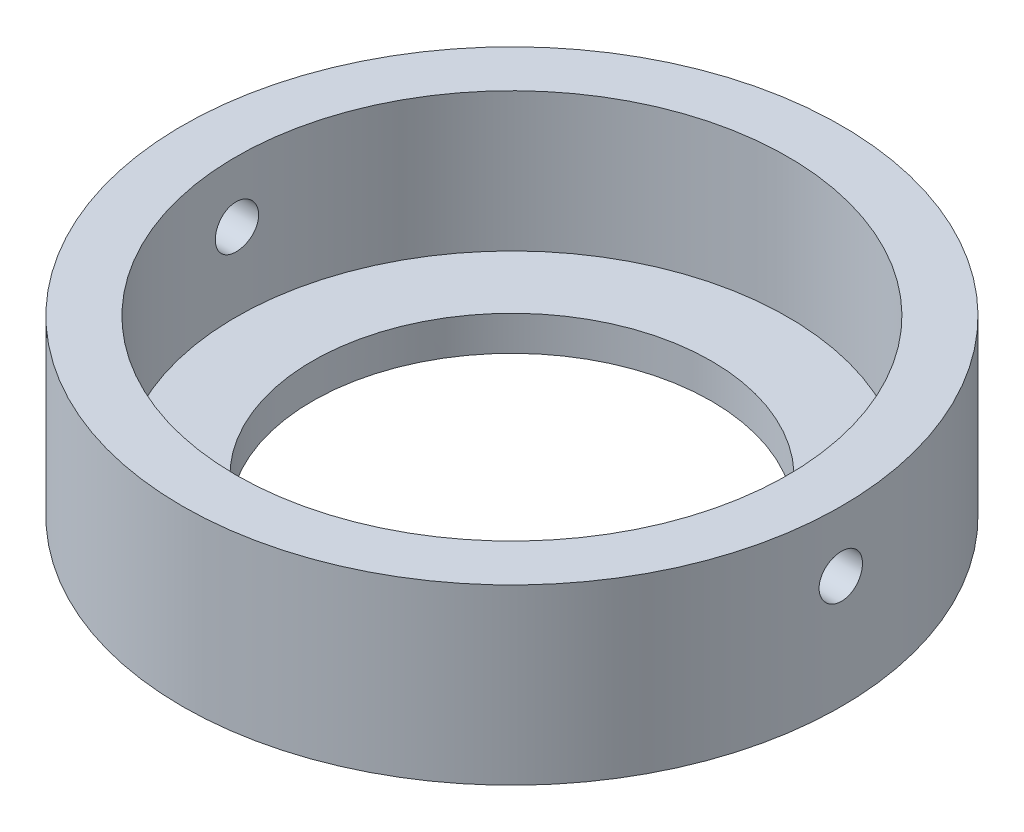
SolidWorks part; units mm, degrees
ref_plane "前视基准面" through (0, 0, 0) normal (0, 0, 1) x (1, 0, 0)
ref_plane "上视基准面" through (0, 0, 0) normal (0, 1, 0) x (1, 0, 0)
ref_plane "右视基准面" through (0, 0, 0) normal (1, 0, 0) x (0, 0, -1)
other "Configuration Table"
sketch "草图1" plane through (0, 0, 0) normal (0, 1, 0) x (1, 0, 0)
  circle A0 centre (0, 0) radius 19
  dimension "D1" = 38
extrude "凸台-拉伸1" add sketch "草图1" along normal blind 2
sketch "草图2" plane through (0, 2, 0) normal (0, 1, 0) x (1, 0, 0)
  circle A0 centre (0, 0) radius 19
  circle A1 centre (0, 0) radius 15.9
  dimension "D1" = 31.8
extrude "凸台-拉伸2" add sketch "草图2" along normal blind 8
sketch "草图3" plane through (0, 0, 0) normal (0, -1, 0) x (1, 0, 0)
  circle A0 centre (0, 0) radius 11.5
  dimension "D1" = 23
extrude "切除-拉伸1" cut sketch "草图3" against normal blind 6
sketch "草图4" plane through (0, 10, 0) normal (0, 1, 0) x (1, 0, 0)
  line L0 (0, 0) -> (0, 19) construction
  line L1 (0, 0) -> (19, 0) construction
  line L2 (0, 0) -> (-19, 0) construction
  circle A0 centre (0, 0) radius 19 construction
sketch3d "3D草图1"
  point P0 (0, 6, -19)
  point P1 (19, 6.5, 0)
  point P5 (-19, 6.5, 0)
  dimension "D1" = 3.5
  dimension "D2" = 4
  dimension "D3" = 3.5
ref_plane "基准面1" through (-19, 0, 0) normal (-1, 0, 0) x (0, 0, 1)
hole_wizard "M3 螺纹孔1" positions "3D草图5" profile "草图10" tap size "M3" standard "GB"
sketch3d "3D草图5"
  point P0 (19, 6.5, 0)
  point P4 (-19, 6.5, 0)
sketch "草图10" plane through (-19, 6.5, 0) normal (0, 1, 0) x (0, 0, 1)
  line L0 (0, 0) -> (0, 44.6511)
  line L1 (0, 44.6511) -> (1.25, 43.9)
  line L2 (1.25, 43.9) -> (1.25, 0.275)
  line L3 (1.25, 0.275) -> (1.525, 0)
  line L5 (1.525, 0) -> (0, 0)
  line L6 (-1.25, 0.275) -> (-1.525, 0) construction
  line L10 (0, 44.6511) -> (-1.25, 43.9) construction
  line L11 (0, -6.35) -> (0, 107.95) construction
  dimension "螺纹孔钻头直径" = 2.5
  dimension "螺纹孔钻头深度" = 43.9
  dimension "近端锥形沉头孔直径" = 3.05
  dimension "近端锥形沉头孔角度" = 90
  dimension "导头角度" = 118
cosmetic thread "孔螺纹线3" parameters "D1"=42.4, "D2"=3
